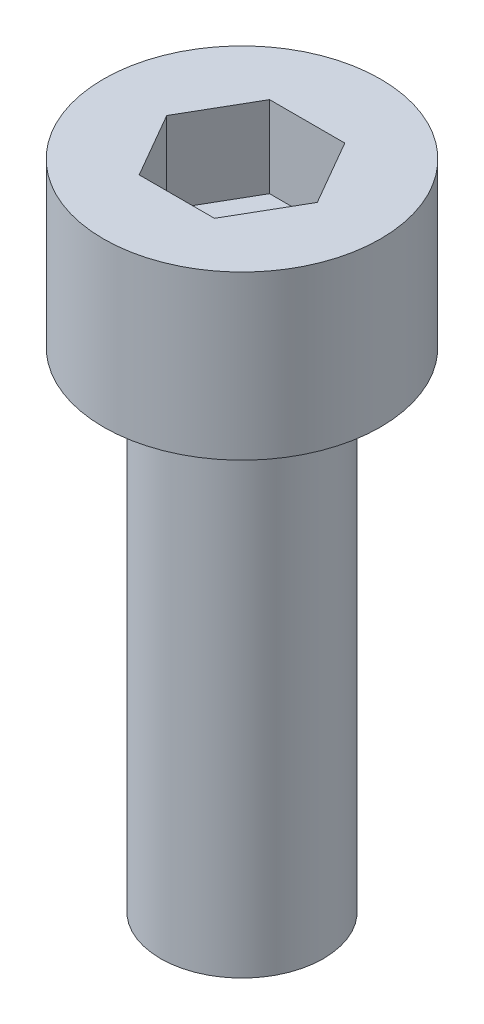
SolidWorks part; units mm, degrees
material "AISI 1020 Steel, Cold Rolled"
ref_plane "Płaszczyzna przednia" through (0, 0, 0) normal (0, 0, 1) x (1, 0, 0)
ref_plane "Płaszczyzna górna" through (0, 0, 0) normal (0, 1, 0) x (1, 0, 0)
ref_plane "Płaszczyzna prawa" through (0, 0, 0) normal (1, 0, 0) x (0, 0, -1)
sketch "Sketch1" plane through (0, 0, 0) normal (0, 0, 1) x (1, 0, 0)
  line L0 (0, 0) -> (2.5, 0)
  line L1 (2.5, 0) -> (2.5, 15)
  line L2 (2.5, 15) -> (4.25, 15)
  line L3 (4.25, 15) -> (4.25, 20)
  line L4 (4.25, 20) -> (0, 20)
  line L5 (0, 20) -> (0, 0)
  dimension "D1" = 2.5
  dimension "D2" = 15
  dimension "D3" = 5
  dimension "D4" = 4.25
revolve "Revolve1" add sketch "Sketch1" angle 360 about L5
sketch "Sketch2" plane through (0, 20, 0) normal (0, 1, 0) x (1, 0, 0)
  line L1 (1.1547, 2) -> (-1.1547, 2)
  line L2 (-1.1547, 2) -> (-2.3094, 0)
  line L3 (-2.3094, 0) -> (-1.1547, -2)
  line L4 (-1.1547, -2) -> (1.1547, -2)
  line L5 (1.1547, -2) -> (2.3094, 0)
  line L6 (2.3094, 0) -> (1.1547, 2)
  circle A0 centre (0, 0) radius 2 construction
  dimension "D1" = 4
extrude "Cut-Extrude1" cut sketch "Sketch2" against normal blind 2.5
